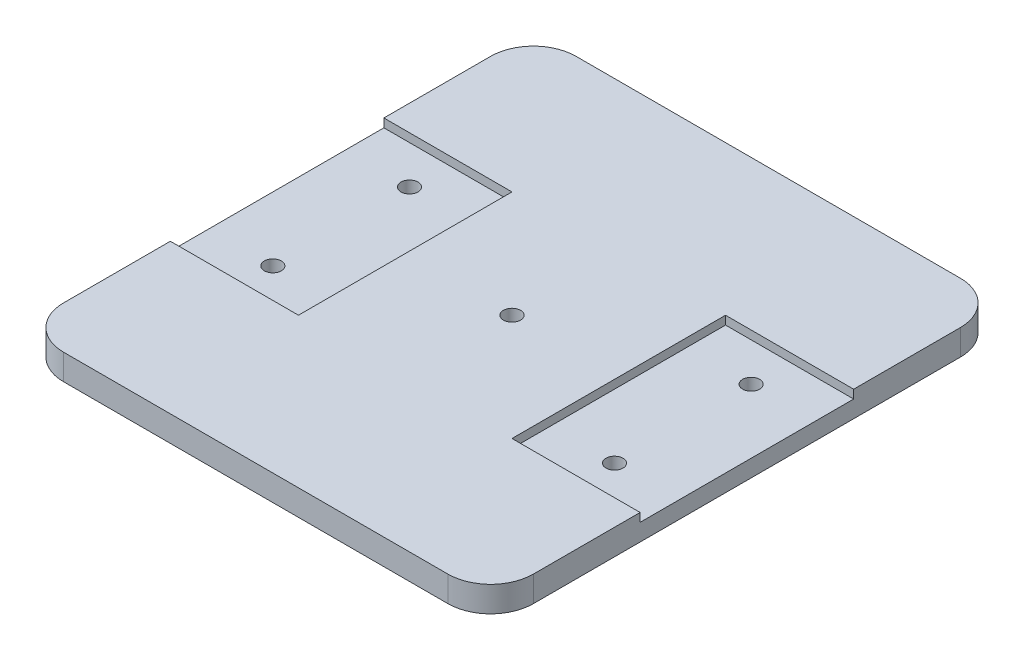
SolidWorks part; units mm, degrees
ref_plane "Front Plane" through (0, 0, 0) normal (0, 0, 1) x (1, 0, 0)
ref_plane "Top Plane" through (0, 0, 0) normal (0, 1, 0) x (1, 0, 0)
ref_plane "Right Plane" through (0, 0, 0) normal (1, 0, 0) x (0, 0, -1)
sketch "Sketch2" plane through (0, 0, 0) normal (0, 1, 0) x (1, 0, 0)
  line L1 (-78.125, 24.375) -> (-23.125, 24.375)
  line L2 (-78.125, 24.375) -> (-78.125, -35.625)
  line L3 (-78.125, -35.625) -> (-23.125, -35.625)
  line L4 (-23.125, 24.375) -> (-23.125, -35.625)
  dimension "D1" = 60
  dimension "D2" = 55
extrude "Boss-Extrude1" add sketch "Sketch2" along normal blind 3
sketch "Sketch3" plane through (0, 3, 0) normal (0, 1, 0) x (1, 0, 0)
  line L0 (-78.125, 24.375) -> (-78.125, -35.625) construction
  line L1 (-78.125, 6.875) -> (-63.125, 6.875)
  line L2 (-78.125, 6.875) -> (-78.125, -18.125)
  line L3 (-78.125, -18.125) -> (-63.125, -18.125)
  line L4 (-63.125, 6.875) -> (-63.125, -18.125)
  line L5 (-23.125, 24.375) -> (-78.125, 24.375) construction
  dimension "D1" = 25
  dimension "D2" = 15
  dimension "D3" = 17.5
extrude "Cut-Extrude1" cut sketch "Sketch3" against normal blind 1
sketch "Sketch4" plane through (0, 3, 0) normal (0, 1, 0) x (1, 0, 0)
  line L0 (-63.125, 6.875) -> (-78.125, 6.875) construction
  line L1 (-78.125, 6.875) -> (-78.125, -18.125) construction
  line L2 (-78.125, -18.125) -> (-63.125, -18.125) construction
  circle A0 centre (-70.625, 2.375) radius 1
  circle A1 centre (-70.625, -13.625) radius 1
  dimension "D2" = 2
  dimension "D4" = 4.5
  dimension "D1" = 4.5
  dimension "D3" = 7.5
extrude "Cut-Extrude3" cut sketch "Sketch4" against normal blind 5
fillet "Fillet1" radius 5 4 edges at (-78.125, 1.5, -24.375) (-23.125, 1.5, -24.375) (-23.125, 1.5, 35.625) (-78.125, 1.5, 35.625)
sketch "Sketch5" plane through (0, 3, 0) normal (0, 1, 0) x (1, 0, 0)
  line L0 (-28.125, 24.375) -> (-73.125, 24.375) construction
  line L1 (-78.125, 19.375) -> (-78.125, 6.875) construction
  circle A0 centre (-50.625, -5.625) radius 1
  dimension "D1" = 30
  dimension "D2" = 27.5
extrude "Cut-Extrude4" cut sketch "Sketch5" against normal blind 5
sketch "Sketch6" plane through (0, 3, 0) normal (0, 1, 0) x (1, 0, 0)
  line L0 (-23.125, -30.625) -> (-23.125, 19.375) construction
  line L1 (-23.125, 6.875) -> (-38.125, 6.875)
  line L2 (-23.125, 6.875) -> (-23.125, -18.125)
  line L3 (-23.125, -18.125) -> (-38.125, -18.125)
  line L4 (-38.125, 6.875) -> (-38.125, -18.125)
  line L5 (-28.125, 24.375) -> (-73.125, 24.375) construction
  dimension "D1" = 15
  dimension "D2" = 25
  dimension "D3" = 17.5
extrude "Cut-Extrude5" cut sketch "Sketch6" against normal blind 1
sketch "Sketch7" plane through (0, 2, 0) normal (0, 1, 0) x (1, 0, 0)
  line L0 (-23.125, 6.875) -> (-38.125, 6.875) construction
  line L2 (-38.125, 6.875) -> (-38.125, -18.125) construction
  line L4 (-38.125, -18.125) -> (-23.125, -18.125) construction
  circle A0 centre (-30.625, 2.375) radius 1
  circle A1 centre (-30.625, -13.625) radius 1
  dimension "D1" = 4.5
  dimension "D3" = 4.5
  dimension "D2" = 7.5
extrude "Cut-Extrude6" cut sketch "Sketch7" against normal blind 2
